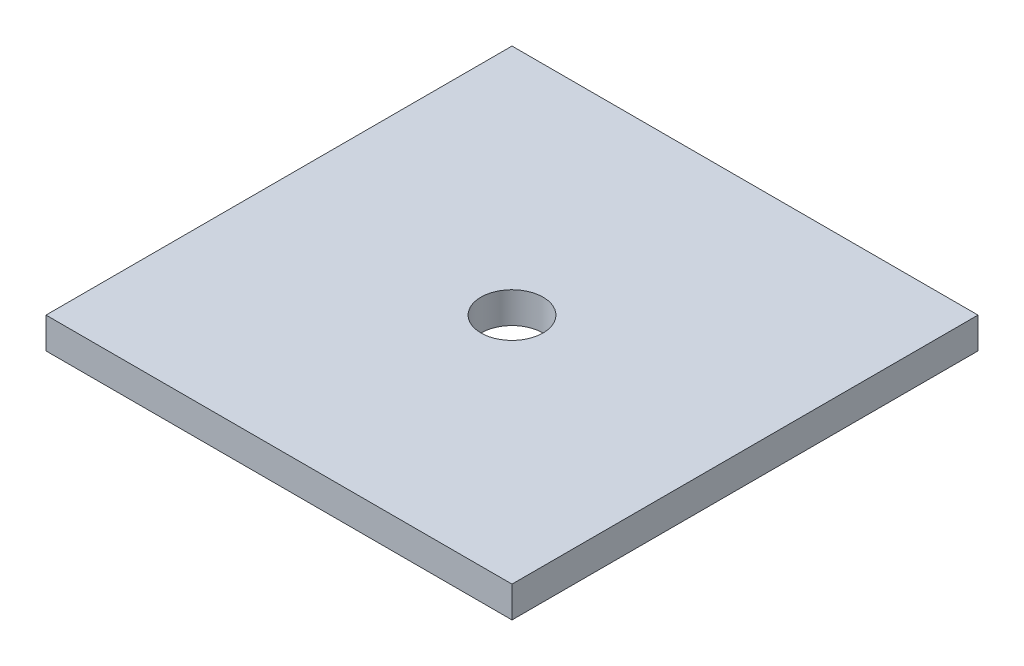
SolidWorks part; units mm, degrees
ref_plane "Front" through (0, 0, 0) normal (0, 0, 1) x (1, 0, 0)
ref_plane "Top" through (0, 0, 0) normal (0, 1, 0) x (1, 0, 0)
ref_plane "Right" through (0, 0, 0) normal (1, 0, 0) x (0, 0, -1)
sketch "草图1" plane through (0, 0, 0) normal (0, 1, 0) x (1, 0, 0)
  line L1 (30, -30) -> (-30, -30)
  line L2 (30, -30) -> (30, 30)
  line L3 (30, 30) -> (-30, 30)
  line L4 (-30, -30) -> (-30, 30)
  line L5 (30, -30) -> (-30, 30) construction
  line L6 (30, 30) -> (-30, -30) construction
  circle A0 centre (0, 0) radius 4
  point P0 (0, 0)
  point P8 (1.493, 7.1498)
  dimension "D3" = 8
  dimension "D1" = 60
  dimension "D2" = 60
  dimension "D4" = 0
  dimension "D5" = 0
extrude "凸台-拉伸1" add sketch "草图1" along normal blind 4
